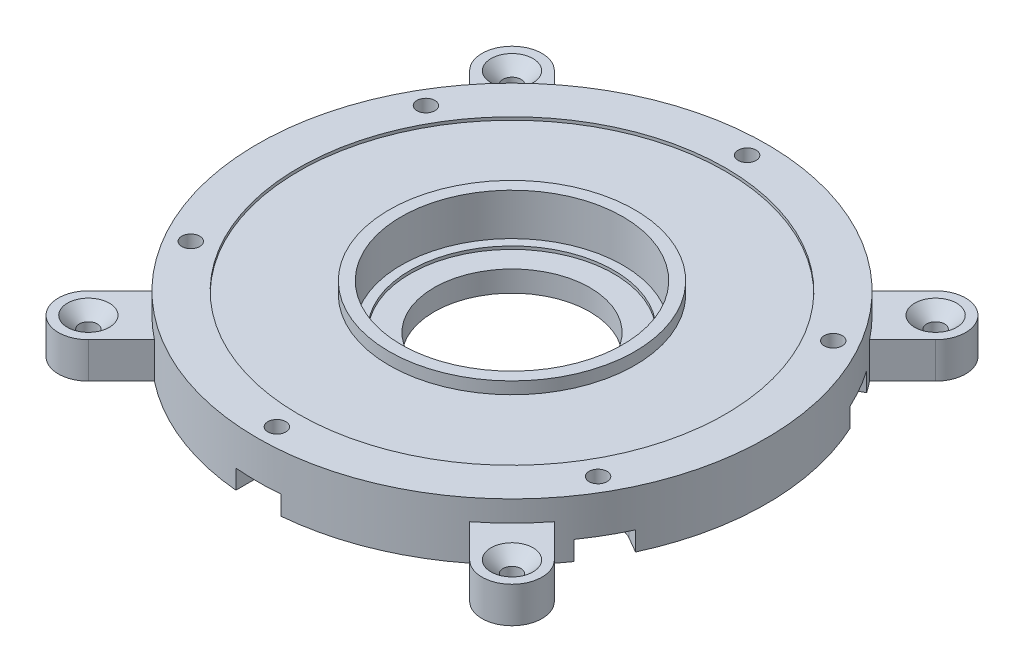
SolidWorks part; units mm, degrees
ref_plane "Plano frontal" through (0, 0, 0) normal (0, 0, 1) x (1, 0, 0)
ref_plane "Plano superior" through (0, 0, 0) normal (0, 1, 0) x (1, 0, 0)
ref_plane "Plano direito" through (0, 0, 0) normal (1, 0, 0) x (0, 0, -1)
sketch "Esboço1" plane through (0, 0, 0) normal (0, 1, 0) x (1, 0, 0)
  circle A0 centre (0, 0) radius 42.5
  dimension "D1" = 85
extrude "Ressalto-extrusão1" add sketch "Esboço1" along normal blind 9
sketch "Esboço2" plane through (0, 0, 0) normal (1, 0, 0) x (0, 0, -1)
  line L0 (0, 0) -> (-13, 0)
  line L1 (-13, 0) -> (-13, 3.5)
  line L2 (-13, 3.5) -> (-17, 3.5)
  line L3 (-17, 3.5) -> (-17, 4)
  line L4 (-17, 4) -> (-18.5, 4)
  line L5 (-18.5, 4) -> (-18.5, 9)
  line L6 (42.5, 9) -> (-42.5, 9) construction
  line L7 (-18.5, 9) -> (0, 9)
  line L8 (0, 9) -> (0, 0)
  dimension "D1" = 13
  dimension "D2" = 3.5
  dimension "D3" = 17
  dimension "D4" = 0.5
  dimension "D5" = 18.5
revolve "Corte-Revolução1" cut sketch "Esboço2" angle 360 about L8
sketch "Esboço3" plane through (0, 9, 0) normal (0, 1, 0) x (1, 0, 0)
  circle A0 centre (0, 0) radius 18.5 construction
  circle A1 centre (0, 0) radius 18.5
  circle A2 centre (0, 0) radius 20.5
  dimension "D1" = 41
extrude "Ressalto-extrusão2" add sketch "Esboço3" along normal blind 2
sketch "Esboço4" plane through (0, 0, 0) normal (0, -1, 0) x (1, 0, 0)
  line L0 (0, 0) -> (0, 39.25) construction
  line L1 (-3.75, 39.25) -> (-3.75, 42.3342)
  line L2 (3.75, 39.25) -> (3.75, 42.3342)
  arc A0 (-3.75, 39.25) -> (3.75, 39.25) centre (0, 39.25) ccw
  circle A1 centre (0, 0) radius 42.5 construction
  arc A2 (3.75, 42.3342) -> (-3.75, 42.3342) centre (0, 0) ccw
  dimension "D2" = 7.5
  dimension "D1" = 39.25
extrude "Corte-extrusão1" cut sketch "Esboço4" against normal blind 3.2
sketch "Esboço9" plane through (0, 9, 0) normal (0, 1, 0) x (1, 0, 0)
  circle A0 centre (0, 0) radius 42.5
  circle A1 centre (0, 0) radius 35.625
  circle A2 centre (0, 0) radius 42.5 construction
  dimension "D1" = 71.25
extrude "Ressalto-extrusão4" add sketch "Esboço9" along normal blind 0.5
sketch "Esboço5" plane through (0, 3.2, 0) normal (0, -1, 0) x (1, 0, 0)
  circle A0 centre (0, 39.25) radius 1.5
  dimension "D1" = 3
extrude "Corte-extrusão2" cut sketch "Esboço5" against normal blind 10
pattern_circular "PadrãoCircular1" count 6 over 360 about axis through (0, 0, 0) along (0, 1, 0) of "Corte-extrusão2", "Corte-extrusão1"
sketch "Esboço6" plane through (0, 0, 0) normal (0, -1, 0) x (1, 0, 0)
  line L0 (0, 0) -> (0, 42.5) construction
  line L1 (0, 0) -> (35.3553, 35.3553) construction
  line L2 (31.8198, 38.8909) -> (26.3078, 33.3789)
  line L3 (38.8909, 31.8198) -> (33.3789, 26.3078)
  arc A0 (3.75, 42.3342) -> (-3.75, 42.3342) centre (0, 0) ccw construction
  arc A2 (0, 42.5) -> (26.3078, 33.3789) centre (0, 0) ccw
  circle A3 centre (0, 0) radius 42.5 construction
  arc A4 (38.8909, 31.8198) -> (31.8198, 38.8909) centre (35.3553, 35.3553) ccw
  arc M23 (34.7875, 24.4147) -> (3.75, 42.3342) centre (0, 0) ccw
  dimension "D2" = 10
  dimension "D1" = 45
  dimension "D3" = 50
extrude "Ressalto-extrusão3" add sketch "Esboço6" against normal blind 6 contours L3 A4 L2 M23
sketch "Esboço8" plane through (0, 0, 0) normal (0, -1, 0) x (1, 0, 0)
  circle A0 centre (35.3553, 35.3553) radius 1.5
  arc A1 (38.8909, 31.8198) -> (31.8198, 38.8909) centre (35.3553, 35.3553) ccw construction
  dimension "D1" = 3
extrude "Corte-extrusão3" cut sketch "Esboço8" against normal blind 10
pattern_circular "PadrãoCircular2" count 4 over 360 about axis through (0, 0, 0) along (0, 1, 0) of "Corte-extrusão3", "Ressalto-extrusão3"
chamfer "Chanfro1" distance 2 angle 45 4 edges at (35.3553, 6, -36.8553) (-35.3553, 6, -36.8553) (-35.3553, 6, 33.8553) (35.3553, 6, 33.8553)
